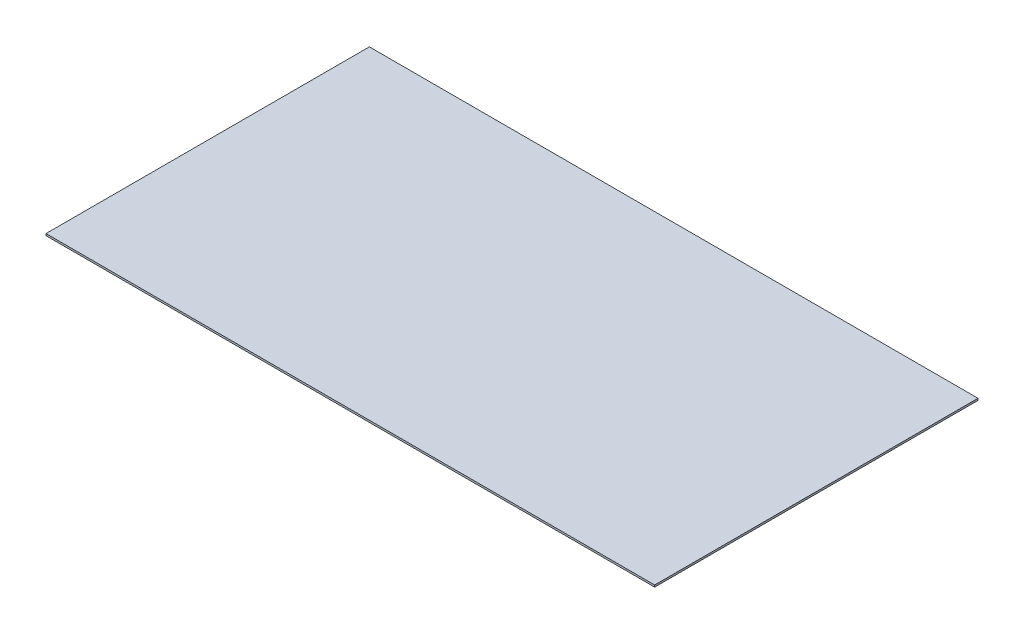
SolidWorks part; units mm, degrees
ref_plane "Front Plane" through (0, 0, 0) normal (0, 0, 1) x (1, 0, 0)
ref_plane "Top Plane" through (0, 0, 0) normal (0, 1, 0) x (1, 0, 0)
ref_plane "Right Plane" through (0, 0, 0) normal (1, 0, 0) x (0, 0, -1)
sketch "Sketch1" plane through (0, 0, 0) normal (0, 1, 0) x (1, 0, 0)
  line L1 (0, 0) -> (406.4, 0)
  line L2 (0, 0) -> (0, 254)
  line L3 (0, 254) -> (406.4, 254)
  line L4 (406.4, 0) -> (406.4, 254)
  line L5 (406.4, 0) -> (812.8, 0)
  line L6 (406.4, 0) -> (406.4, 254)
  line L7 (406.4, 254) -> (812.8, 254)
  line L8 (812.8, 0) -> (812.8, 254)
  line L9 (0, 254) -> (406.4, 254)
  line L10 (0, 254) -> (0, 431.8)
  line L11 (0, 431.8) -> (406.4, 431.8)
  line L12 (406.4, 254) -> (406.4, 431.8)
  line L13 (406.4, 254) -> (812.8, 254)
  line L14 (406.4, 254) -> (406.4, 431.8)
  line L15 (406.4, 431.8) -> (812.8, 431.8)
  line L16 (812.8, 254) -> (812.8, 431.8)
  dimension "D1" = 406.4
  dimension "D2" = 254
  dimension "D3" = 406.4
  dimension "D4" = 177.8
extrude "Boss-Extrude1" add sketch "Sketch1" along normal blind 2.54 contours L1 L4 L3 L2 | L3 L12 L11 L10 | L7 L16 L15 L12 | L5 L8 L7 L4
